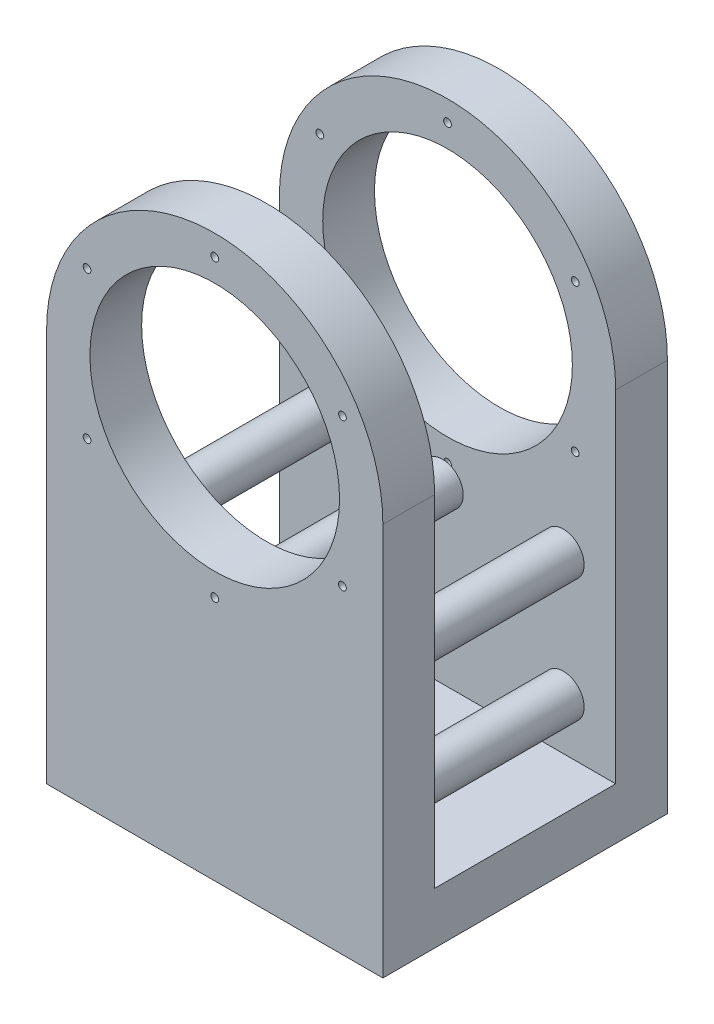
SolidWorks part; units mm, degrees
ref_plane "前视基准面" through (0, 0, 0) normal (0, 0, 1) x (1, 0, 0)
ref_plane "上视基准面" through (0, 0, 0) normal (0, 1, 0) x (1, 0, 0)
ref_plane "右视基准面" through (0, 0, 0) normal (1, 0, 0) x (0, 0, -1)
sketch "草图1" plane through (0, 0, 0) normal (0, 0, 1) x (1, 0, 0)
  line L2 (-65, -103.5259) -> (-65, 120.2086)
  line L4 (65, -103.5259) -> (65, 120.2086)
  arc A0 (-65, -103.5259) -> (65, -103.5259) centre (0, -103.5259) ccw
  arc A1 (-65, 120.2086) -> (65, 120.2086) centre (0, 120.2086) cw
  circle A2 centre (0, 120.2086) radius 48.25
  circle A3 centre (0, -103.5259) radius 48.25
  point P0 (0, 0)
  dimension "D1" = 96.5
extrude "凸台-拉伸1" add sketch "草图1" along normal blind 20
sketch "草图2" plane through (0, 0, 0) normal (0, 0, -1) x (-1, 0, 0)
  line L0 (0, 0) -> (172.2863, 0) construction
  line L1 (0, 1336.9171) -> (0, 168.4586) construction
  line L13 (0, -151.7759) -> (0, -184.8527) construction
  line L20 (0, 71.9586) -> (0, -55.2759) construction
  circle A8 centre (-44.8126, 55.5315) radius 8
  circle A9 centre (-44.8126, -39.6571) radius 8
  circle A10 centre (48.6601, -39.6571) radius 8
  circle A11 centre (48.6601, 55.5315) radius 8
  circle A12 centre (1.9238, 55.5315) radius 8
  circle A13 centre (1.9238, -39.6571) radius 8
  circle A14 centre (-44.8126, 7.9372) radius 8
  circle A15 centre (48.6601, 7.9372) radius 8
  dimension "D2" = 16
  dimension "D3" = 16
  dimension "D4" = 16
  dimension "D5" = 16
  dimension "D6" = 16
  dimension "D7" = 16
  dimension "D8" = 16
  dimension "D9" = 16
extrude "凸台-拉伸2" add sketch "草图2" along normal blind 70
sketch "草图3" plane through (0, 0, -70) normal (0, 0, -1) x (-1, 0, 0)
  line L2 (65, -103.5259) -> (65, 120.2086)
  line L3 (-65, 120.2086) -> (-65, -103.5259)
  line L4 (65, -103.5259) -> (65, 120.2086)
  line L5 (-65, 120.2086) -> (-65, -103.5259)
  circle A0 centre (0, 120.2086) radius 48.25 construction
  circle A1 centre (0, -103.5259) radius 48.25 construction
  arc A2 (-65, -103.5259) -> (65, -103.5259) centre (0, -103.5259) ccw
  arc A3 (65, 120.2086) -> (-65, 120.2086) centre (0, 120.2086) ccw
  arc A4 (-65, -103.5259) -> (65, -103.5259) centre (0, -103.5259) ccw
  arc A5 (65, 120.2086) -> (-65, 120.2086) centre (0, 120.2086) ccw
  circle A6 centre (0, 120.2086) radius 48.25
  circle A7 centre (0, -103.5259) radius 48.25
  dimension "D1" = 0
extrude "凸台-拉伸3" add sketch "草图3" along normal blind 20
sketch "草图4" plane through (0, 0, 20) normal (0, 0, 1) x (1, 0, 0)
  line L0 (-65, -31.6571) -> (65, -31.6571)
  line L3 (65, -103.5259) -> (65, 120.2086)
  line L4 (-65, 120.2086) -> (-65, -103.5259)
  line L5 (65, -103.5259) -> (65, -31.6571)
  line L6 (-65, -31.6571) -> (-65, -103.5259)
  circle A0 centre (-48.6601, -39.6571) radius 8 construction
  circle A1 centre (-1.9238, -39.6571) radius 8 construction
  circle A2 centre (44.8126, -39.6571) radius 8 construction
  circle A3 centre (-48.6601, -39.6571) radius 8
  circle A4 centre (-1.9238, -39.6571) radius 8
  circle A5 centre (44.8126, -39.6571) radius 8
  arc A8 (-65, -103.5259) -> (65, -103.5259) centre (0, -103.5259) ccw
  arc A9 (65, 120.2086) -> (-65, 120.2086) centre (0, 120.2086) ccw
  arc A10 (-65, -103.5259) -> (65, -103.5259) centre (0, -103.5259) ccw
  arc M7 (-65, -103.5259) -> (65, -103.5259) centre (0, -103.5259) ccw
  line M8 (65, -103.5259) -> (65, 120.2086)
  line M10 (-65, 120.2086) -> (-65, -103.5259)
  circle M11 centre (0, -103.5259) radius 48.25
  dimension "D1" = 0
extrude "切除-拉伸2" cut sketch "草图4" against normal through all contours L0 A5 A4 A3 M10 M7 M8 M11 | M11 | A4 | A5 | A3
sketch "草图5" plane through (0, 0, 0) normal (0, 0, -1) x (-1, 0, 0)
  line L0 (-65, -11.6571) -> (65, -11.6571)
  line L3 (-65, -31.6571) -> (65, -31.6571)
  line L4 (65, -31.6571) -> (65, 120.2086)
  line L5 (-65, 120.2086) -> (-65, -31.6571)
  line L6 (-65, -31.6571) -> (65, -31.6571)
  line L7 (65, -31.6571) -> (65, -11.6571)
  line L8 (-65, -11.6571) -> (-65, -31.6571)
  arc A1 (65, 120.2086) -> (-65, 120.2086) centre (0, 120.2086) ccw
  dimension "D2" = 20
  dimension "D1" = 0
extrude "凸台-拉伸4" add sketch "草图5" along normal up to surface (70 mm away) contours L6 L7 L0 L8 up to face at (-48.25, 120.2086, -70)
sketch "草图6" plane through (0, -31.6571, 0) normal (0, -1, 0) x (1, 0, 0)
  circle A0 centre (0, -35) radius 30
  point P10 (0, -35)
  dimension "D2" = 60
extrude "切除-拉伸3" cut sketch "草图6" against normal blind 20
sketch "草图7" plane through (0, -31.6571, 0) normal (0, -1, 0) x (1, 0, 0)
  circle A0 centre (0, -35) radius 30 construction
  circle A1 centre (0, -35) radius 30
extrude "凸台-拉伸5" add sketch "草图7" against normal blind 20
sketch "草图8" plane through (0, -31.6571, 0) normal (0, -1, 0) x (1, 0, 0)
  circle A0 centre (0, -35) radius 30 construction
  circle A3 centre (0, -17.75) radius 1.65
  circle A4 centre (14.9389, -26.375) radius 1.65
  circle A5 centre (14.9389, -43.625) radius 1.65
  circle A6 centre (0, -52.25) radius 1.65
  circle A7 centre (-14.9389, -43.625) radius 1.65
  circle A8 centre (-14.9389, -26.375) radius 1.65
  point P17 (0, -35)
  dimension "D1" = 6
  dimension "D2" = 3.3
extrude "凸台-拉伸7" add sketch "草图8" along normal blind 10
sketch "草图9" plane through (0, -31.6571, 0) normal (0, -1, 0) x (1, 0, 0)
  circle A1 centre (0, -52.25) radius 1.65 construction
  circle A2 centre (14.9389, -43.625) radius 1.65 construction
  circle A3 centre (14.9389, -26.375) radius 1.65 construction
  circle A4 centre (-14.9389, -43.625) radius 1.65 construction
  circle A5 centre (-14.9389, -26.375) radius 1.65 construction
  circle A6 centre (0, -17.75) radius 1.65 construction
  circle A7 centre (0, -52.25) radius 1.65
  circle A8 centre (14.9389, -43.625) radius 1.65
  circle A9 centre (14.9389, -26.375) radius 1.65
  circle A10 centre (-14.9389, -43.625) radius 1.65
  circle A11 centre (-14.9389, -26.375) radius 1.65
  circle A12 centre (0, -17.75) radius 1.65
extrude "切除-拉伸4" cut sketch "草图9" against normal up to next and the other way up to next
sketch "草图10" plane through (0, 0, 0) normal (0, 0, -1) x (-1, 0, 0)
  circle A5 centre (0, 177.2086) radius 1.5
  circle A6 centre (49.3634, 148.7086) radius 1.5
  circle A7 centre (49.3634, 91.7086) radius 1.5
  circle A8 centre (0, 63.2086) radius 1.5
  circle A9 centre (-49.3634, 91.7086) radius 1.5
  circle A10 centre (-49.3634, 148.7086) radius 1.5
  point P17 (0, 120.2086)
  dimension "D3" = 3
  dimension "D1" = 6
extrude "切除-拉伸5" cut sketch "草图10" against normal through all
sketch "草图11" plane through (0, 0, -70) normal (0, 0, 1) x (1, 0, 0)
  circle A0 centre (49.3634, 148.7086) radius 1.5 construction
  circle A1 centre (0, 177.2086) radius 1.5 construction
  circle A2 centre (-49.3634, 148.7086) radius 1.5 construction
  circle A3 centre (0, 63.2086) radius 1.5 construction
  circle A4 centre (-49.3634, 91.7086) radius 1.5 construction
  circle A5 centre (49.3634, 91.7086) radius 1.5 construction
  circle A6 centre (49.3634, 148.7086) radius 1.5
  circle A7 centre (0, 177.2086) radius 1.5
  circle A8 centre (-49.3634, 148.7086) radius 1.5
  circle A9 centre (0, 63.2086) radius 1.5
  circle A10 centre (-49.3634, 91.7086) radius 1.5
  circle A11 centre (49.3634, 91.7086) radius 1.5
extrude "切除-拉伸6" cut sketch "草图11" against normal through all
